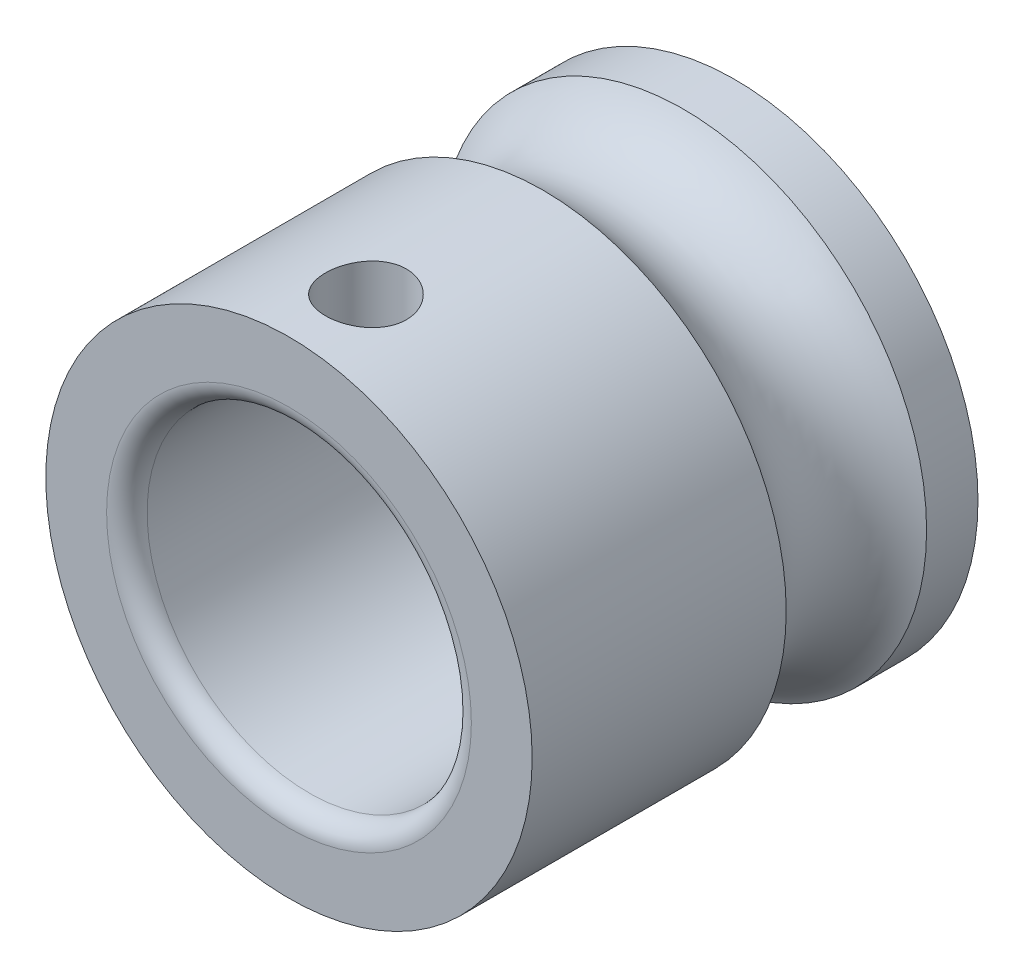
SolidWorks part; units mm, degrees
ref_plane "Front Plane" through (0, 0, 0) normal (0, 0, 1) x (1, 0, 0)
ref_plane "Top Plane" through (0, 0, 0) normal (0, 1, 0) x (1, 0, 0)
ref_plane "Right Plane" through (0, 0, 0) normal (1, 0, 0) x (0, 0, -1)
sketch "Sketch1" plane through (0, 0, 0) normal (0, 0, 1) x (1, 0, 0)
  circle A0 centre (0, 0) radius 4
  circle A1 centre (0, 0) radius 6
  dimension "D1" = 8
  dimension "D2" = 12
extrude "Boss-Extrude1" add sketch "Sketch1" along normal blind 8 and the other way blind 3
sketch "Sketch2" plane through (0, 0, 0) normal (0, 0, 1) x (1, 0, 0)
  circle A1 centre (0, 0) radius 5
  circle A2 centre (0, 0) radius 6
  dimension "D1" = 12
  dimension "D2" = 10
sketch "Sketch3" plane through (0, 0, 0) normal (0, 1, 0) x (1, 0, 0)
  line L0 (0, 3.0363) -> (0, -2.2876) construction
  line L1 (-6, 0) -> (6, 0) construction
  circle A1 centre (-7, 0) radius 2
  dimension "D1" = 4
  dimension "D2" = 7
revolve "Cut-Revolve1" cut sketch "Sketch3" angle 360 about L0
fillet "Fillet1" radius 0.5 2 edges at (4, 0, 8) (4, 0, -3)
sketch "Sketch4" plane through (0, 0, 0) normal (0, 1, 0) x (1, 0, 0)
  line L0 (0, 0) -> (0, -6.7183) construction
  circle A0 centre (0, -6.101) radius 1
  dimension "D1" = 2
extrude "Cut-Extrude2" cut sketch "Sketch4" along normal through all
